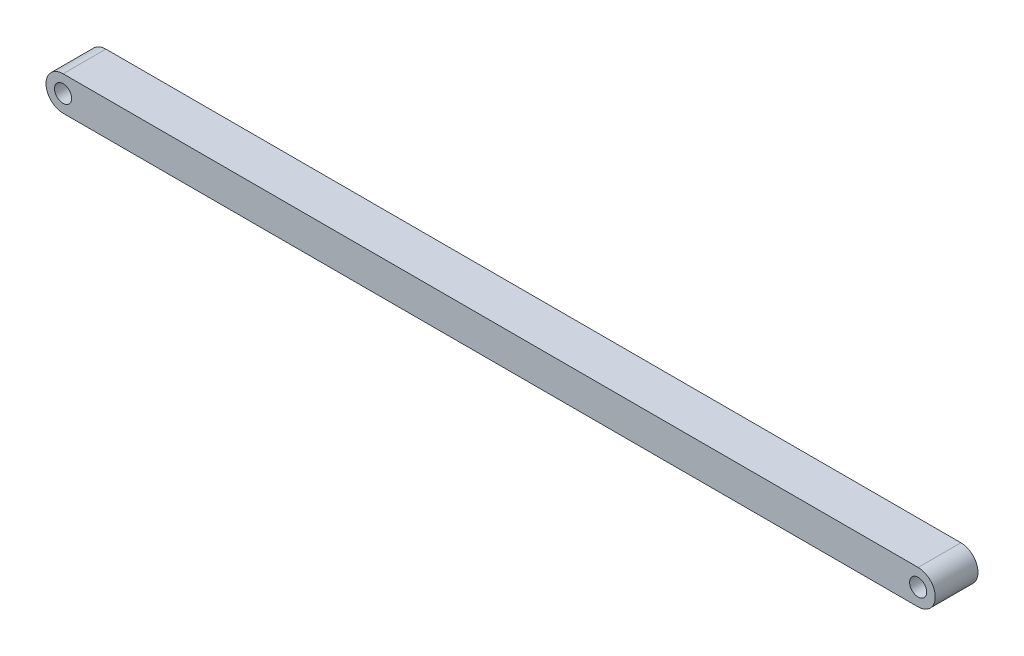
SolidWorks part; units mm, degrees
ref_plane "Front Plane" through (0, 0, 0) normal (0, 0, 1) x (1, 0, 0)
ref_plane "Top Plane" through (0, 0, 0) normal (0, 1, 0) x (1, 0, 0)
ref_plane "Right Plane" through (0, 0, 0) normal (1, 0, 0) x (0, 0, -1)
sketch "Sketch1" plane through (0, 0, 0) normal (0, 0, 1) x (1, 0, 0)
  line L0 (0, 0) -> (100, 0) construction
  line L1 (0, 2) -> (100, 2)
  line L2 (0, -2) -> (100, -2)
  arc A0 (0, 2) -> (0, -2) centre (0, 0) ccw
  arc A1 (100, -2) -> (100, 2) centre (100, 0) ccw
  circle A2 centre (0, 0) radius 1
  circle A3 centre (100, 0) radius 1
  point P3 (50, 0)
  dimension "D2" = 2
  dimension "D3" = 2
  dimension "D4" = 2
  dimension "D1" = 100
extrude "Boss-Extrude1" add sketch "Sketch1" along normal blind 5
